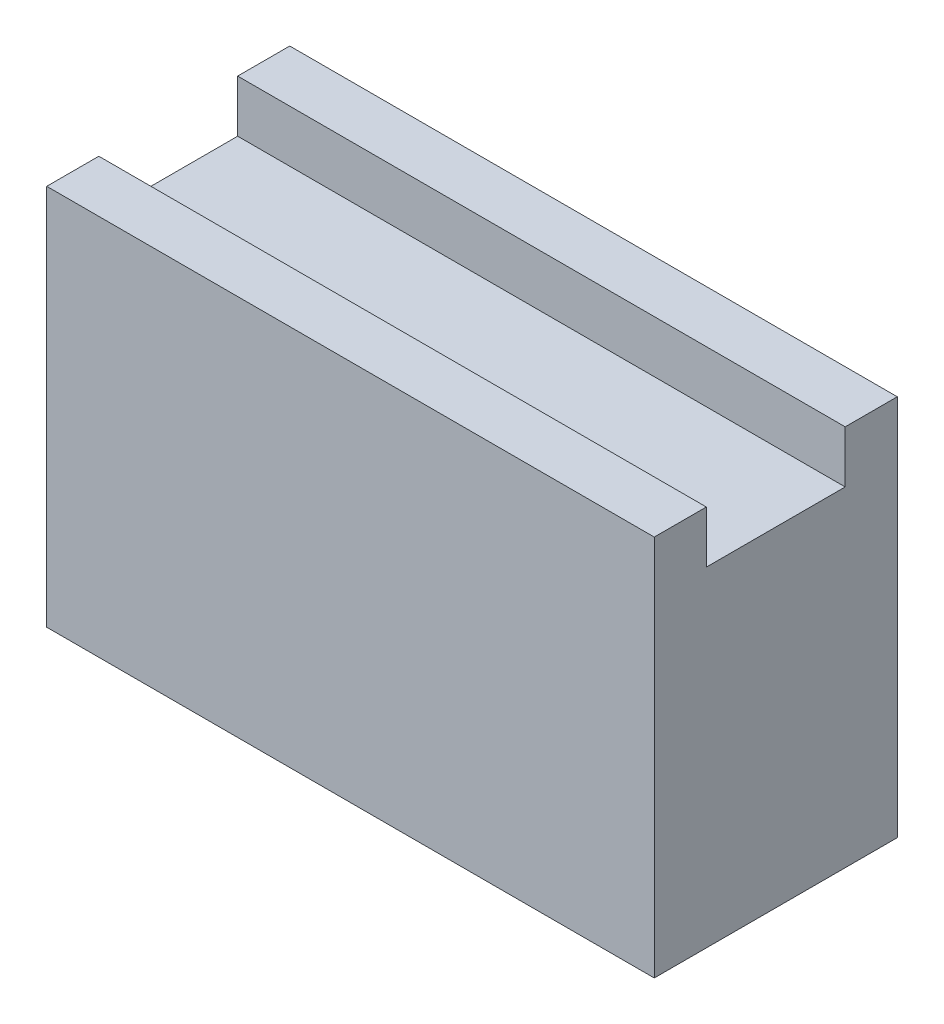
SolidWorks part; units mm, degrees
ref_plane "Front Plane" through (0, 0, 0) normal (0, 0, 1) x (1, 0, 0)
ref_plane "Top Plane" through (0, 0, 0) normal (0, 1, 0) x (1, 0, 0)
ref_plane "Right Plane" through (0, 0, 0) normal (1, 0, 0) x (0, 0, -1)
sketch "Sketch1" plane through (0, 0, 0) normal (1, 0, 0) x (0, 0, -1)
  line L0 (-7, 9.5) -> (-7, 12.5)
  line L1 (-7, -9.5) -> (7, -9.5)
  line L2 (-7, -9.5) -> (-7, 9.5)
  line L3 (-4, 9.5) -> (4, 9.5)
  line L4 (7, -9.5) -> (7, 9.5)
  line L5 (-7, -9.5) -> (7, 9.5) construction
  line L6 (-7, 9.5) -> (7, -9.5) construction
  line L7 (-7, 12.5) -> (-4, 12.5)
  line L8 (-4, 12.5) -> (-4, 9.5)
  line L9 (7, 9.5) -> (7, 12.5)
  line L10 (7, 12.5) -> (4, 12.5)
  line L11 (4, 12.5) -> (4, 9.5)
  point P0 (0, 0)
  point P12 (0, 9.5)
  dimension "D1" = 19
  dimension "D2" = 8
  dimension "D3" = 3
  dimension "D4" = 3
extrude "Boss-Extrude1" add sketch "Sketch1" against normal blind 35
